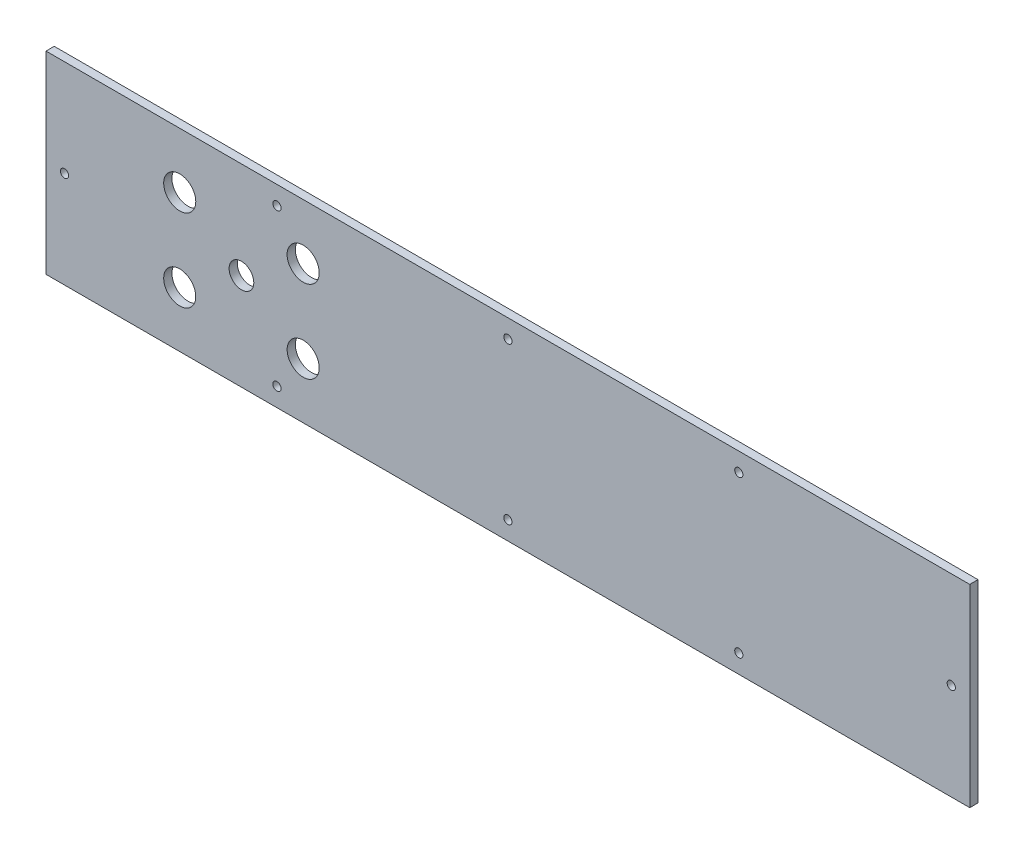
SolidWorks part; units mm, degrees
ref_plane "Piano frontale" through (0, 0, 0) normal (0, 0, 1) x (1, 0, 0)
ref_plane "Piano superiore" through (0, 0, 0) normal (0, 1, 0) x (1, 0, 0)
ref_plane "Piano destro" through (0, 0, 0) normal (1, 0, 0) x (0, 0, -1)
sketch "Schizzo1" plane through (0, 0, 0) normal (0, 0, 1) x (1, 0, 0)
  line L0 (-224.5, 351.6275) -> (-224.5, -66.2585) construction
  line L1 (0, 0) -> (-449, 0)
  line L2 (0, 0) -> (0, 94)
  line L3 (0, 94) -> (-449, 94)
  line L4 (-449, 0) -> (-449, 94)
  line L5 (-384, 47) -> (120.8821, 47) construction
  line L6 (-476.1211, 67) -> (-192.6282, 67) construction
  line L7 (-476.1211, 27) -> (-192.6282, 27) construction
  line L8 (-354, 67) -> (-354, 27) construction
  line L9 (-224.5, 94) -> (-449, 0) construction
  line L10 (-336.75, 47) -> (-336.75, 0) construction
  circle A0 centre (-384, 27) radius 7.8
  circle A1 centre (-9, 47) radius 2
  circle A2 centre (-224.5, 85) radius 2
  circle A3 centre (-440, 47) radius 2
  circle A4 centre (-224.5, 9) radius 2
  circle A5 centre (-324, 27) radius 7.8
  circle A6 centre (-324, 67) radius 7.8
  circle A7 centre (-336.75, 85) radius 2
  circle A8 centre (-384, 67) radius 7.8
  circle A9 centre (-336.75, 9) radius 2
  circle A10 centre (-112.25, 9) radius 2
  circle A11 centre (-112.25, 85) radius 2
  circle A12 centre (-354, 47) radius 6
  point P9 (-224.5, 47)
  dimension "D3" = 4
  dimension "D2" = 4
  dimension "D5" = 65
  dimension "D8" = 4
  dimension "D9" = 9
  dimension "D10" = 12
  dimension "D12" = 15.6
  dimension "D1" = 449
  dimension "314" = 94
  dimension "D4" = 9
  dimension "D6" = 9
  dimension "D7" = 30
  dimension "D11" = 20
extrude "Estrusione-Estrusione1" add sketch "Schizzo1" along normal blind 4
